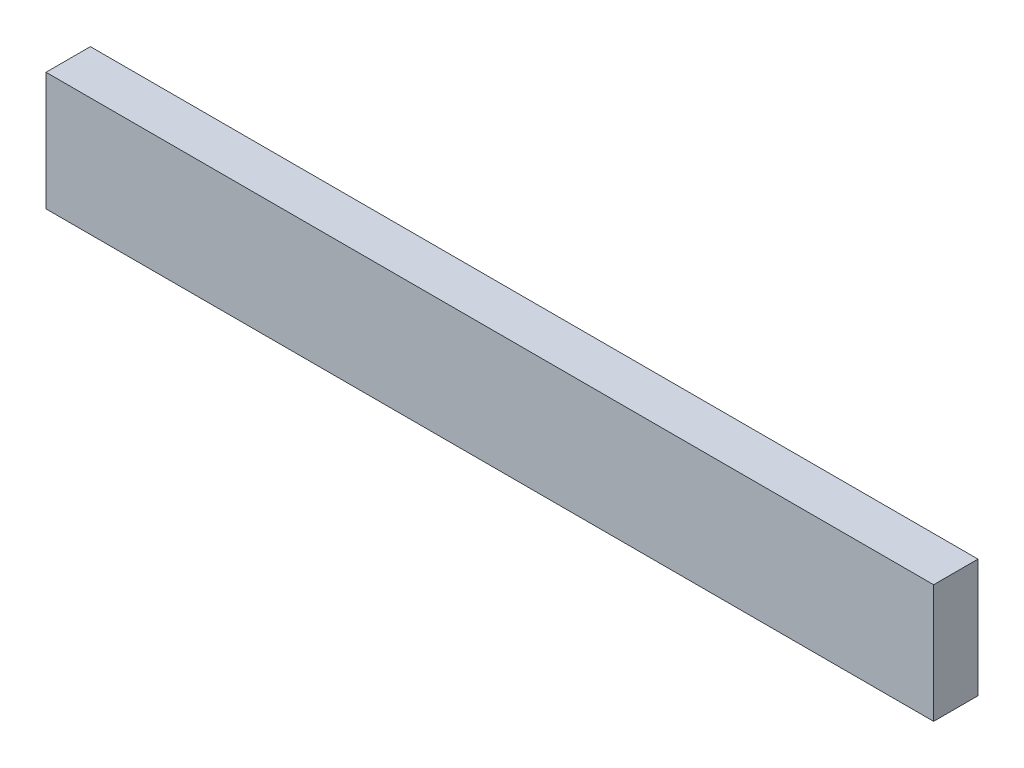
SolidWorks part; units mm, degrees
ref_plane "Front" through (0, 0, 0) normal (0, 0, 1) x (1, 0, 0)
ref_plane "Top" through (0, 0, 0) normal (0, 1, 0) x (1, 0, 0)
ref_plane "Right" through (0, 0, 0) normal (1, 0, 0) x (0, 0, -1)
sketch "Croquis1" plane through (0, 0, 0) normal (0, 0, 1) x (1, 0, 0)
  line L1 (0, 0) -> (60, 0)
  line L2 (0, 0) -> (0, 8)
  line L3 (0, 8) -> (60, 8)
  line L4 (60, 0) -> (60, 8)
  line L5 (0, 0) -> (60, 8) construction
  line L6 (0, 8) -> (60, 0) construction
  point P5 (30, 4)
  dimension "D1" = 8
  dimension "D2" = 60
extrude "Saliente-Extruir1" add sketch "Croquis1" along normal blind 3
